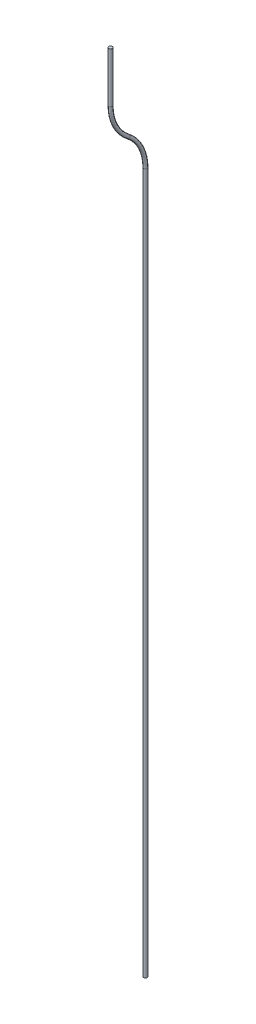
SolidWorks part; units mm, degrees
ref_plane "Front Plane" through (0, 0, 0) normal (0, 0, 1) x (1, 0, 0)
ref_plane "Top Plane" through (0, 0, 0) normal (0, 1, 0) x (1, 0, 0)
ref_plane "Right Plane" through (0, 0, 0) normal (1, 0, 0) x (0, 0, -1)
sketch "Illustrative smooth utility route" plane through (0, 0, 0) normal (1, 0, 0) x (0, 0, -1)
  line L0 (-16.25, 0) -> (-16.25, -16.9)
  line L1 (-4.5, -40.9) -> (-4.5, -276.9)
  arc A0 (-16.25, -16.9) -> (-10.375, -28.9) centre (-1.0572, -16.9) ccw
  arc A1 (-10.375, -28.9) -> (-4.5, -40.9) centre (-19.6928, -40.9) cw
sketch "Utility circular cross section" plane through (0, 0, 0) normal (0, 1, 0) x (1, 0, 0)
  circle A0 centre (0, -16.25) radius 0.6
sweep "Native hollow utility sweep" add profiles "Utility circular cross section" path "Illustrative smooth utility route"
